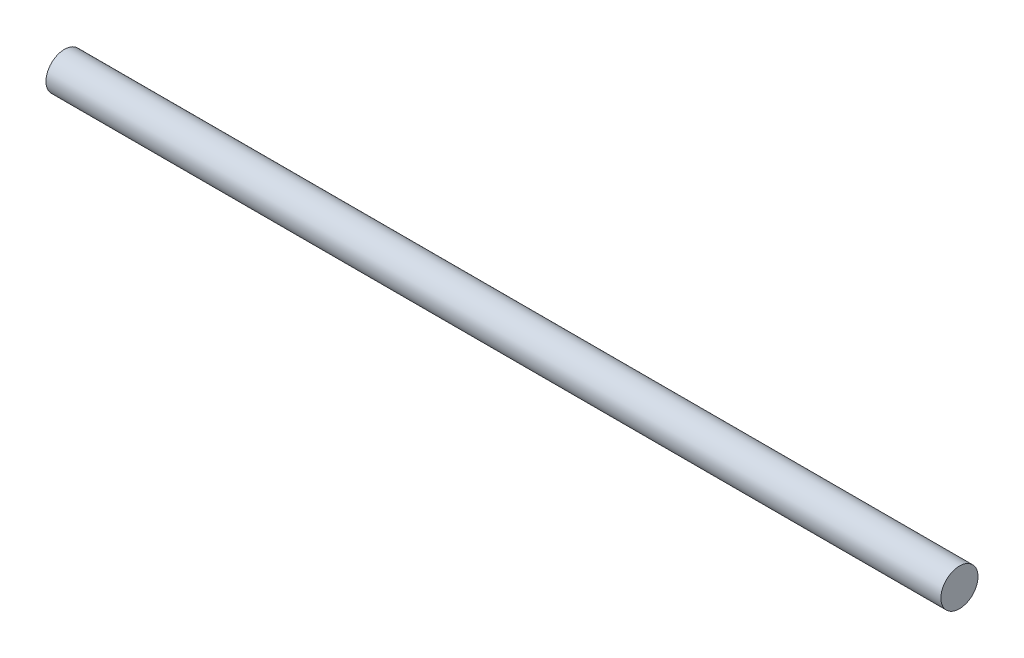
SolidWorks part; units mm, degrees
ref_plane "Front Plane" through (0, 0, 0) normal (0, 0, 1) x (1, 0, 0)
ref_plane "Top Plane" through (0, 0, 0) normal (0, 1, 0) x (1, 0, 0)
ref_plane "Right Plane" through (0, 0, 0) normal (1, 0, 0) x (0, 0, -1)
sketch "Sketch1" plane through (0, 0, 0) normal (1, 0, 0) x (0, 0, -1)
  circle A0 centre (0, 0) radius 50
  dimension "D1" = 100
extrude "Boss-Extrude1" add sketch "Sketch1" along normal blind 2205.6 and the other way blind 207.0273
